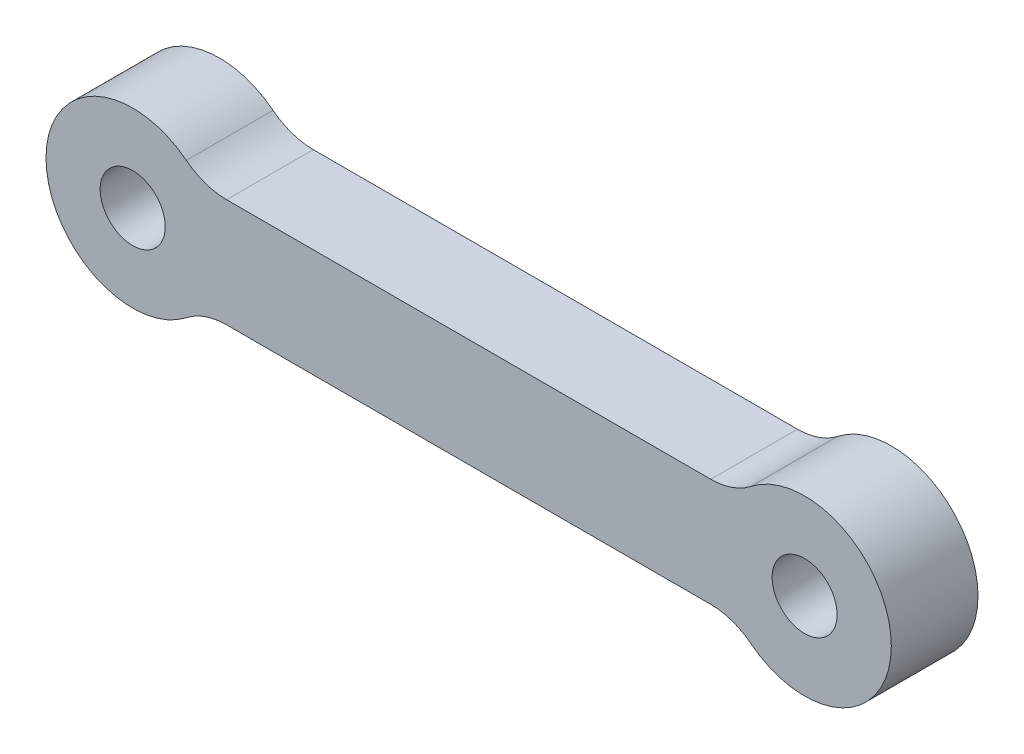
SolidWorks part; units mm, degrees
ref_plane "Front Plane" through (0, 0, 0) normal (0, 0, 1) x (1, 0, 0)
ref_plane "Top Plane" through (0, 0, 0) normal (0, 1, 0) x (1, 0, 0)
ref_plane "Right Plane" through (0, 0, 0) normal (1, 0, 0) x (0, 0, -1)
sketch "Sketch1" plane through (0, 0, 0) normal (0, 0, 1) x (1, 0, 0)
  line L0 (0, 0) -> (0, 6.2183) construction
  line L2 (-11.1699, -2.5) -> (11.1699, -2.5)
  line L4 (-11.1699, 2.5) -> (11.1699, 2.5)
  line L6 (-12.3775, -2.5) -> (12.3775, 2.5) construction
  line L7 (-12.3775, 2.5) -> (12.3775, -2.5) construction
  arc A0 (-13.0256, 3.1429) -> (-13.0256, -3.1429) centre (-15.5, 0) ccw
  circle A1 centre (-15.5, 0) radius 1.5
  circle A4 centre (15.5, 0) radius 1.5
  arc A5 (13.0256, 3.1429) -> (13.0256, -3.1429) centre (15.5, 0) cw
  arc A6 (11.1699, -2.5) -> (13.0256, -3.1429) centre (11.1699, -5.5) cw
  arc A7 (11.1699, 2.5) -> (13.0256, 3.1429) centre (11.1699, 5.5) ccw
  arc A8 (-11.1699, -2.5) -> (-13.0256, -3.1429) centre (-11.1699, -5.5) ccw
  arc A9 (-13.0256, 3.1429) -> (-11.1699, 2.5) centre (-11.1699, 5.5) ccw
  dimension "D1" = 3
  dimension "D2" = 8
  dimension "D5" = 3
  dimension "D3" = 31
  dimension "D4" = 5
extrude "Boss-Extrude1" add sketch "Sketch1" along normal blind 4
